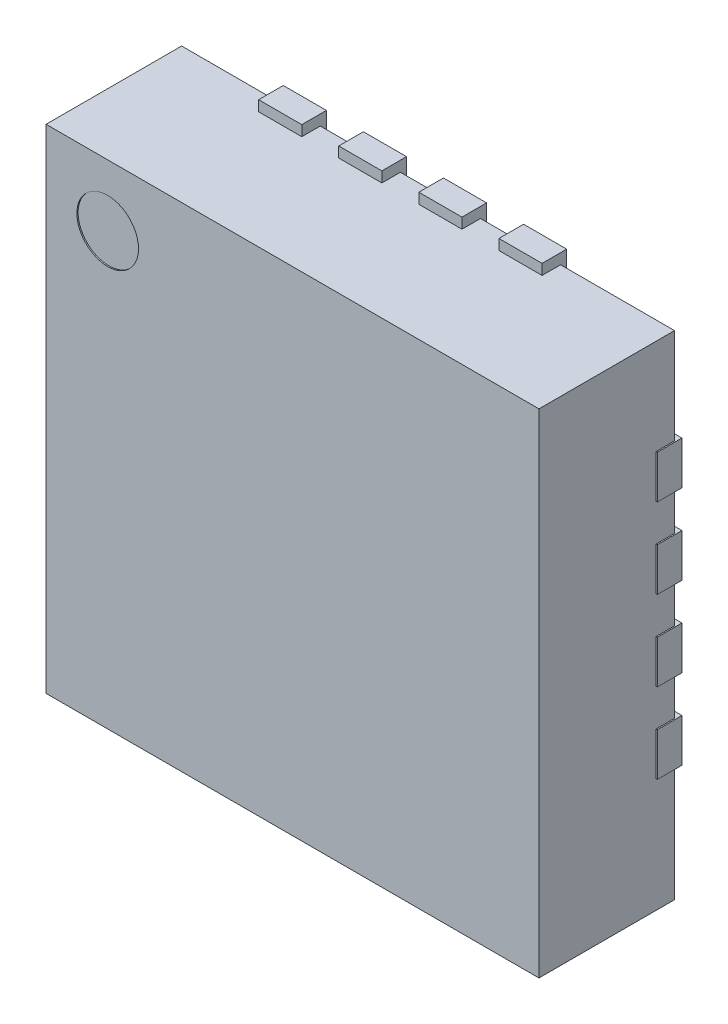
SolidWorks part; units mm, degrees
ref_plane "Plano frontal" through (0, 0, 0) normal (0, 0, 1) x (1, 0, 0)
ref_plane "Plano superior" through (0, 0, 0) normal (0, 1, 0) x (1, 0, 0)
ref_plane "Plano direito" through (0, 0, 0) normal (1, 0, 0) x (0, 0, -1)
ref_plane "Plano1" through (0, 0, 0.05) normal (0, 0, 1) x (1, 0, 0)
sketch "Esboço1" plane through (0, 0, 0.05) normal (0, 0, 1) x (1, 0, 0)
  line L1 (-2, 2) -> (2, 2)
  line L2 (-2, 2) -> (-2, -2)
  line L3 (-2, -2) -> (2, -2)
  line L4 (2, 2) -> (2, -2)
  line L5 (-2, 2) -> (2, -2) construction
  line L6 (-2, -2) -> (2, 2) construction
  point P0 (0, 0)
  dimension "D1" = 4
  dimension "D2" = 4
extrude "Ressalto-extrusão1" add sketch "Esboço1" along normal blind 1.1
sketch "Esboço2" plane through (0, 0, 0) normal (0, 0, 1) x (1, 0, 0)
  line L0 (0, 2) -> (0, -2) construction
  line L7 (2, 2) -> (-2, 2) construction
  line L8 (-2, -2) -> (2, -2) construction
  line L9 (-1.15, -1.635) -> (-0.8, -1.635) construction
  line L10 (-0.8, -2.01) -> (-1.15, -2.01)
  line L11 (-1.15, -2.01) -> (-1.15, -1.635)
  line L12 (-0.975, -2.0402) -> (-0.975, -1.635) construction
  line L13 (-0.8, -2.01) -> (-0.8, -1.635)
  line L14 (-0.5, -2.01) -> (-0.5, -1.635)
  line L15 (-0.15, -2.01) -> (-0.5, -2.01)
  line L16 (-0.15, -2.01) -> (-0.15, -1.635)
  line L17 (0.15, -2.01) -> (0.15, -1.635)
  line L18 (0.5, -2.01) -> (0.15, -2.01)
  line L19 (0.5, -2.01) -> (0.5, -1.635)
  line L20 (0.8, -2.01) -> (0.8, -1.635)
  line L21 (1.15, -2.01) -> (0.8, -2.01)
  line L22 (1.15, -2.01) -> (1.15, -1.635)
  line L23 (-2.085, 0.8) -> (-2.085, 1.15)
  line L24 (-2.085, 1.15) -> (-1.71, 1.15)
  line L25 (-2.085, 0.8) -> (-1.71, 0.8)
  line L26 (-2.085, 0.5) -> (-1.71, 0.5)
  line L27 (-2.085, 0.15) -> (-2.085, 0.5)
  line L28 (-2.085, 0.15) -> (-1.71, 0.15)
  line L29 (-2.085, -0.15) -> (-1.71, -0.15)
  line L30 (-2.085, -0.5) -> (-2.085, -0.15)
  line L31 (-2.085, -0.5) -> (-1.71, -0.5)
  line L32 (-2.085, -0.8) -> (-1.71, -0.8)
  line L33 (-2.085, -1.15) -> (-2.085, -0.8)
  line L34 (-2.085, -1.15) -> (-1.71, -1.15)
  line L35 (0.725, 2.085) -> (1.075, 2.085)
  line L36 (1.075, 2.085) -> (1.075, 1.71)
  line L37 (0.725, 2.085) -> (0.725, 1.71)
  line L38 (0.425, 2.085) -> (0.425, 1.71)
  line L39 (0.075, 2.085) -> (0.425, 2.085)
  line L40 (0.075, 2.085) -> (0.075, 1.71)
  line L41 (-0.225, 2.085) -> (-0.225, 1.71)
  line L42 (-0.575, 2.085) -> (-0.225, 2.085)
  line L43 (-0.575, 2.085) -> (-0.575, 1.71)
  line L44 (-0.875, 2.085) -> (-0.875, 1.71)
  line L45 (-1.225, 2.085) -> (-0.875, 2.085)
  line L46 (-1.225, 2.085) -> (-1.225, 1.71)
  line L47 (2.01, -0.725) -> (2.01, -1.075)
  line L48 (2.01, -1.075) -> (1.635, -1.075)
  line L49 (2.01, -0.725) -> (1.635, -0.725)
  line L50 (2.01, -0.425) -> (1.635, -0.425)
  line L51 (2.01, -0.075) -> (2.01, -0.425)
  line L52 (2.01, -0.075) -> (1.635, -0.075)
  line L53 (2.01, 0.225) -> (1.635, 0.225)
  line L54 (2.01, 0.575) -> (2.01, 0.225)
  line L55 (2.01, 0.575) -> (1.635, 0.575)
  line L56 (2.01, 0.875) -> (1.635, 0.875)
  line L57 (2.01, 1.225) -> (2.01, 0.875)
  line L58 (2.01, 1.225) -> (1.635, 1.225)
  arc A0 (-0.8, -1.635) -> (-1.15, -1.635) centre (-0.975, -1.635) ccw
  arc A1 (-0.15, -1.635) -> (-0.5, -1.635) centre (-0.325, -1.635) ccw
  arc A2 (0.5, -1.635) -> (0.15, -1.635) centre (0.325, -1.635) ccw
  arc A3 (1.15, -1.635) -> (0.8, -1.635) centre (0.975, -1.635) ccw
  arc A4 (-1.71, 0.8) -> (-1.71, 1.15) centre (-1.71, 0.975) ccw
  arc A5 (-1.71, 0.15) -> (-1.71, 0.5) centre (-1.71, 0.325) ccw
  arc A6 (-1.71, -0.5) -> (-1.71, -0.15) centre (-1.71, -0.325) ccw
  arc A7 (-1.71, -1.15) -> (-1.71, -0.8) centre (-1.71, -0.975) ccw
  arc A8 (0.725, 1.71) -> (1.075, 1.71) centre (0.9, 1.71) ccw
  arc A9 (0.075, 1.71) -> (0.425, 1.71) centre (0.25, 1.71) ccw
  arc A10 (-0.575, 1.71) -> (-0.225, 1.71) centre (-0.4, 1.71) ccw
  arc A11 (-1.225, 1.71) -> (-0.875, 1.71) centre (-1.05, 1.71) ccw
  arc A12 (1.635, -0.725) -> (1.635, -1.075) centre (1.635, -0.9) ccw
  arc A13 (1.635, -0.075) -> (1.635, -0.425) centre (1.635, -0.25) ccw
  arc A14 (1.635, 0.575) -> (1.635, 0.225) centre (1.635, 0.4) ccw
  arc A15 (1.635, 1.225) -> (1.635, 0.875) centre (1.635, 1.05) ccw
  point P0 (0, 0)
  point P96 (-0.0375, 0.0375)
  dimension "D3" = 0.35
  dimension "D4" = 0.375
  dimension "D5" = 0.975
  dimension "D6" = 0.01
  dimension "D8" = 0.65
  dimension "D7" = 4
  dimension "D9" = 4
extrude "Ressalto-extrusão2" add sketch "Esboço2" along normal blind 0.2
sketch "Esboço3" plane through (0, 0, 1.15) normal (0, 0, 1) x (1, 0, 0)
  line L0 (2, 2) -> (-2, 2) construction
  line L2 (-2, 2) -> (-2, -2) construction
  circle A0 centre (-1.5, 1.5) radius 0.25
  dimension "D3" = 0.5
  dimension "D1" = 0.5
  dimension "D2" = 0.5
extrude "Corte-extrusão1" cut sketch "Esboço3" against normal blind 0.01
